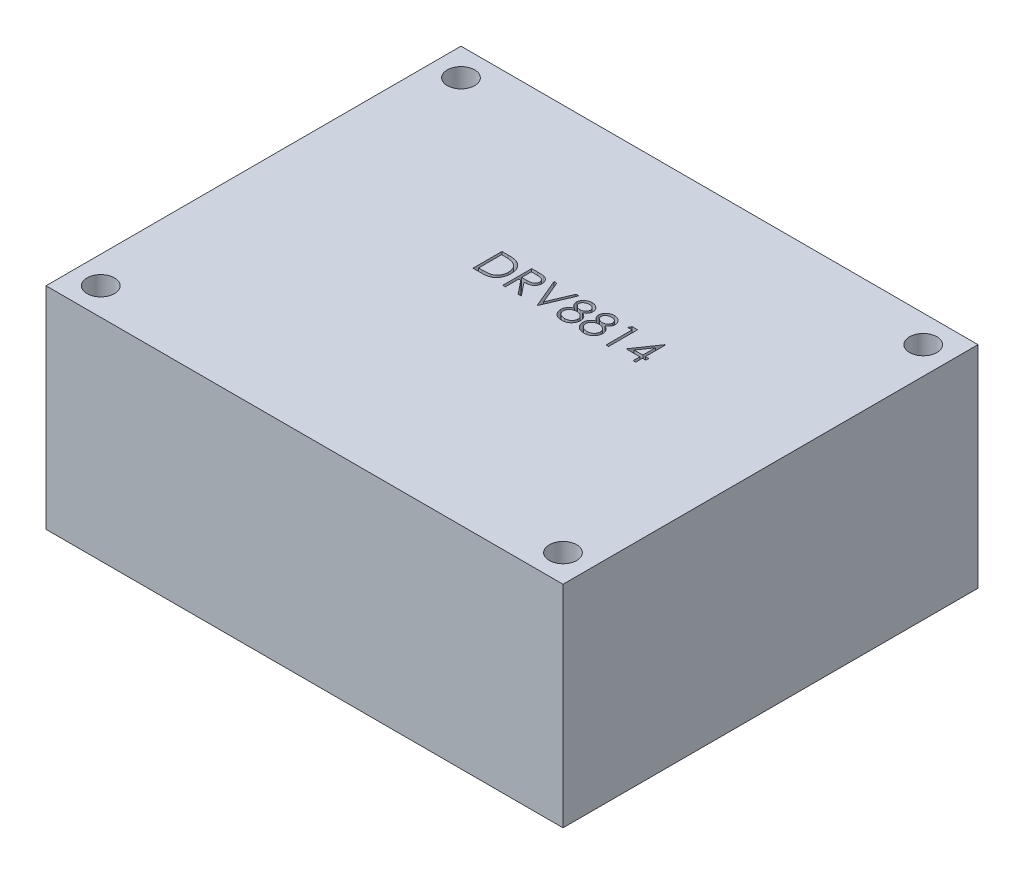
SolidWorks part; units mm, degrees
ref_plane "Front Plane" through (0, 0, 0) normal (0, 0, 1) x (1, 0, 0)
ref_plane "Top Plane" through (0, 0, 0) normal (0, 1, 0) x (1, 0, 0)
ref_plane "Right Plane" through (0, 0, 0) normal (1, 0, 0) x (0, 0, -1)
sketch "Sketch1" plane through (0, 0, 0) normal (0, 1, 0) x (1, 0, 0)
  line L1 (0, 0) -> (56.642, 0)
  line L2 (0, 0) -> (0, 45.466)
  line L3 (0, 45.466) -> (56.642, 45.466)
  line L4 (56.642, 0) -> (56.642, 45.466)
  dimension "D1" = 56.642
  dimension "D2" = 45.466
extrude "Boss-Extrude1" add sketch "Sketch1" along normal blind 23.114
sketch "Sketch2" plane through (0, 0, 0) normal (0, -1, 0) x (-1, 0, 0)
  line L0 (0, 45.466) -> (0, 0) construction
  line L1 (-56.642, 22.733) -> (0, 22.733) construction
  line L2 (-56.642, 0) -> (-56.642, 45.466) construction
  line L3 (-28.321, 45.466) -> (-28.321, 0) construction
  line L4 (-56.642, 45.466) -> (0, 45.466) construction
  line L5 (0, 0) -> (-56.642, 0) construction
  circle A0 centre (-3, 42.466) radius 1.5
  circle A1 centre (-53.642, 42.466) radius 1.5
  circle A2 centre (-3, 3) radius 1.5
  circle A3 centre (-53.642, 3) radius 1.5
  dimension "D1" = 3
  dimension "D2" = 3
  dimension "D3" = 3
extrude "Cut-Extrude1" cut sketch "Sketch2" against normal through all
sketch "Sketch3" plane through (0, 23.114, 0) normal (0, 1, 0) x (1, 0, 0)
  text T0 "DRV8814"
extrude "Cut-Extrude2" cut sketch "Sketch3" against normal blind 1.27
